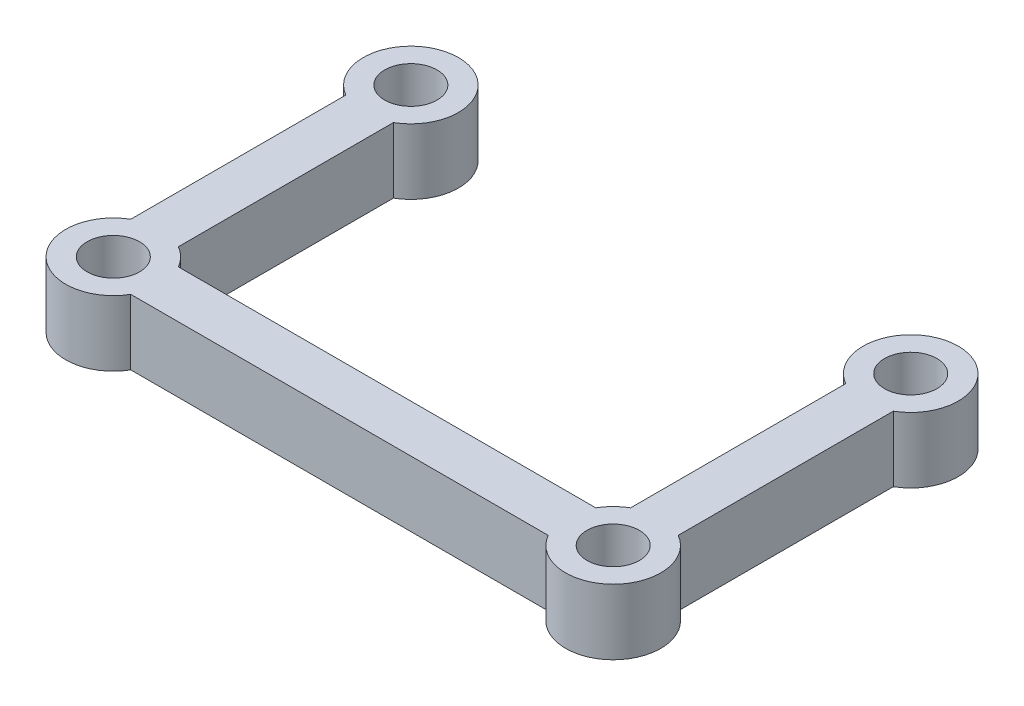
SolidWorks part; units mm, degrees
ref_plane "Front Plane" through (0, 0, 0) normal (0, 0, 1) x (1, 0, 0)
ref_plane "Top Plane" through (0, 0, 0) normal (0, 1, 0) x (1, 0, 0)
ref_plane "Right Plane" through (0, 0, 0) normal (1, 0, 0) x (0, 0, -1)
sketch "Main" plane through (0, 0, 0) normal (0, 1, 0) x (1, 0, 0)
  line L0 (-21, 12.5) -> (-21, 0) construction
  line L1 (-21, 0) -> (0, 0) construction
  line L2 (0, 0) -> (0, 12.5) construction
  line L3 (-19.2679, 1) -> (-1.7321, 1)
  line L4 (-19.2679, -1) -> (-1.7321, -1)
  line L5 (-22, 10.7679) -> (-22, 1.7321)
  line L6 (-20, 10.7679) -> (-20, 1.7321)
  line L7 (-1, 10.7679) -> (-1, 1.7321)
  line L8 (1, 10.7679) -> (1, 1.7321)
  arc A0 (-1, 1.7321) -> (-1.7321, 1) centre (0, 0) ccw
  arc A1 (-22, 1.7321) -> (-19.2679, -1) centre (-21, 0) ccw
  arc A2 (-20, 10.7679) -> (-22, 10.7679) centre (-21, 12.5) ccw
  arc A3 (1, 10.7679) -> (-1, 10.7679) centre (0, 12.5) ccw
  arc A6 (-1.7321, -1) -> (1, 1.7321) centre (0, 0) ccw
  arc A7 (-19.2679, 1) -> (-20, 1.7321) centre (-21, 0) ccw
  point P1 (0, 0)
  dimension "D2" = 4
  dimension "D10" = 2
  dimension "D11" = 2
  dimension "D1" = 12.5
  dimension "D3" = 21
  dimension "D4" = 1
  dimension "D5" = 1
  dimension "D6" = 1
  dimension "D7" = 1
  dimension "D8" = 1
  dimension "D9" = 1
extrude "ExtudeMain" add sketch "Main" along normal blind 2.75
sketch "Sketch2" plane through (0, 2.75, 0) normal (0, 1, 0) x (1, 0, 0)
  circle A0 centre (-21, 12.5) radius 1.1
  circle A1 centre (0, 12.5) radius 1.1
  circle A2 centre (0, 0) radius 1.1
  circle A3 centre (-21, 0) radius 1.1
  dimension "D1" = 2.2
extrude "PiHoles" cut sketch "Sketch2" against normal up to next
equation "\"Thick\" = 1mm"
equation "\"D4@Main\" = \"Thick\""
equation "\"D5@Main\" = \"Thick\""
equation "\"D7@Main\" = \"Thick\""
equation "\"D8@Main\" = \"Thick\""
equation "\"D9@Main\" = \"Thick\""
equation "\"CircSize\"= 4mm"
equation "\"D2@Main\" = \"CircSize\""
equation "\"D10@Main\" = \"CircSize\" / 2"
equation "\"D11@Main\" = \"CircSize\" / 2"
equation "\"D6@Main\"=\"Thick\""
